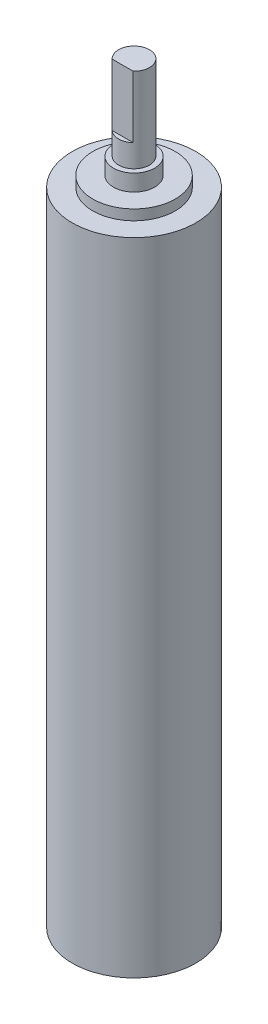
SolidWorks part; units mm, degrees
ref_plane "Front Plane" through (0, 0, 0) normal (0, 0, 1) x (1, 0, 0)
ref_plane "Top Plane" through (0, 0, 0) normal (0, 1, 0) x (1, 0, 0)
ref_plane "Right Plane" through (0, 0, 0) normal (1, 0, 0) x (0, 0, -1)
sketch "Sketch1" plane through (0, 0, 0) normal (0, 1, 0) x (1, 0, 0)
  circle A0 centre (0, 0) radius 3
  dimension "D1" = 6
extrude "motorAndGearbox" add sketch "Sketch1" along normal blind 26.9
sketch "Sketch2" plane through (0, 0, 0) normal (0, -1, 0) x (1, 0, 0)
  circle A1 centre (0, 0) radius 3
  circle A2 centre (0, 0) radius 3
  dimension "D1" = 0
extrude "encoder" add sketch "Sketch2" along normal blind 4.2
sketch "Sketch3" plane through (0, 26.9, 0) normal (0, 1, 0) x (1, 0, 0)
  circle A0 centre (0, 0) radius 2
  dimension "D1" = 4
extrude "Boss-Extrude3" add sketch "Sketch3" along normal blind 0.5
sketch "Sketch4" plane through (0, 27.4, 0) normal (0, 1, 0) x (1, 0, 0)
  circle A0 centre (0, 0) radius 1
  dimension "D1" = 2
extrude "Boss-Extrude4" add sketch "Sketch4" along normal blind 0.8
sketch "Sketch5" plane through (0, 28.2, 0) normal (0, 1, 0) x (1, 0, 0)
  circle A0 centre (0, 0) radius 0.75
  dimension "D1" = 1.5
extrude "Boss-Extrude5" add sketch "Sketch5" along normal blind 4.1
sketch "Sketch6" plane through (0, 32.3, 0) normal (0, 1, 0) x (1, 0, 0)
  line L0 (-0.5099, -0.55) -> (0.5099, -0.55)
  circle A1 centre (0, 0) radius 0.75
  arc A2 (0.5099, -0.55) -> (-0.5099, -0.55) centre (0, 0) ccw
  point P5 (0, 0.75)
  dimension "D2" = 1.3
  dimension "D1" = 0
extrude "Cut-Extrude1" cut sketch "Sketch6" against normal blind 3 flip side to cut
